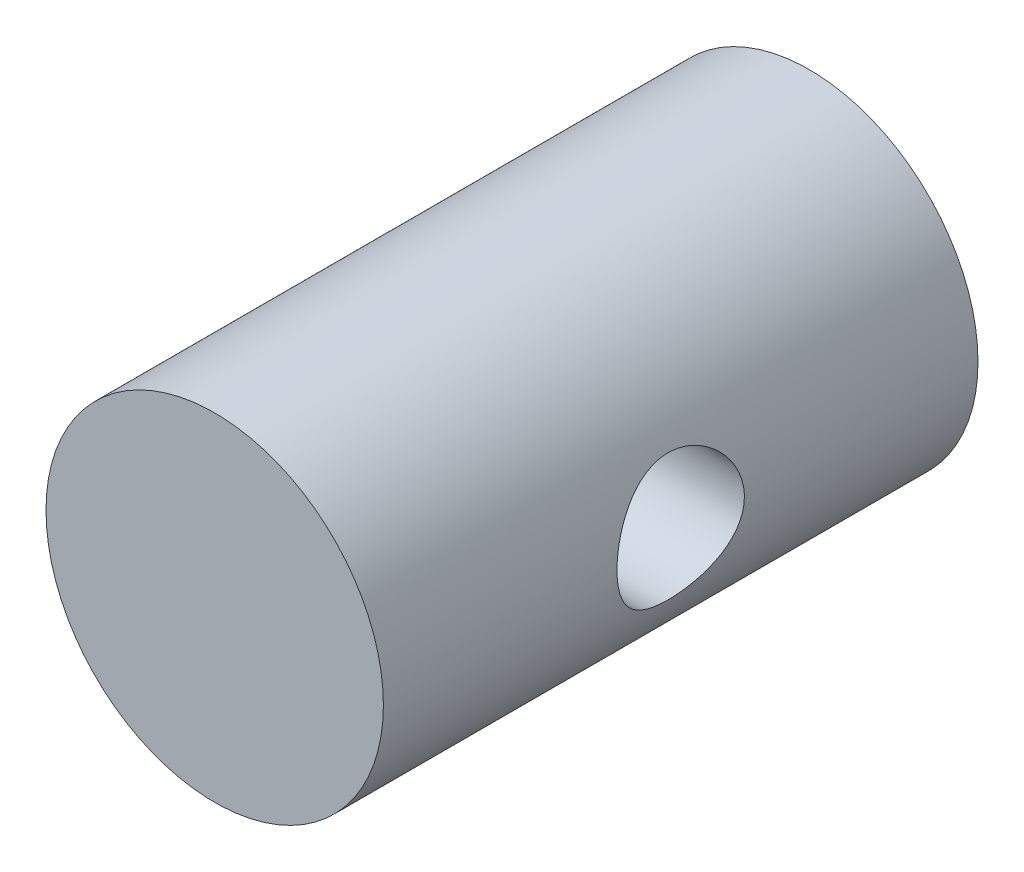
SolidWorks part; units mm, degrees
ref_plane "Front Plane" through (0, 0, 0) normal (1, 0, 0) x (0, 1, 0)
ref_plane "Top Plane" through (0, 0, 0) normal (0, 0, 1) x (0, 1, 0)
ref_plane "Right Plane" through (0, 0, 0) normal (0, 1, 0) x (-1, 0, 0)
sketch "Sketch1" plane through (0, 0, 0) normal (0, 0, 1) x (0, 1, 0)
  circle A0 centre (0, 0) radius 12.6111
  dimension "D1" = 25.2222
extrude "Boss-Extrude1" add sketch "Sketch1" along normal blind 44.45
sketch "Sketch2" plane through (0, 0, 0) normal (1, 0, 0) x (0, 1, 0)
  line L0 (0, 0) -> (0, 22.225) construction
  line L1 (0, 22.225) -> (0, 44.45) construction
  line L2 (12.6111, 44.45) -> (-12.6111, 44.45) construction
  circle A0 centre (0, 22.225) radius 4.7625
  dimension "D1" = 9.525
extrude "Cut-Extrude1" cut sketch "Sketch2" against normal through all both and the other way through all
